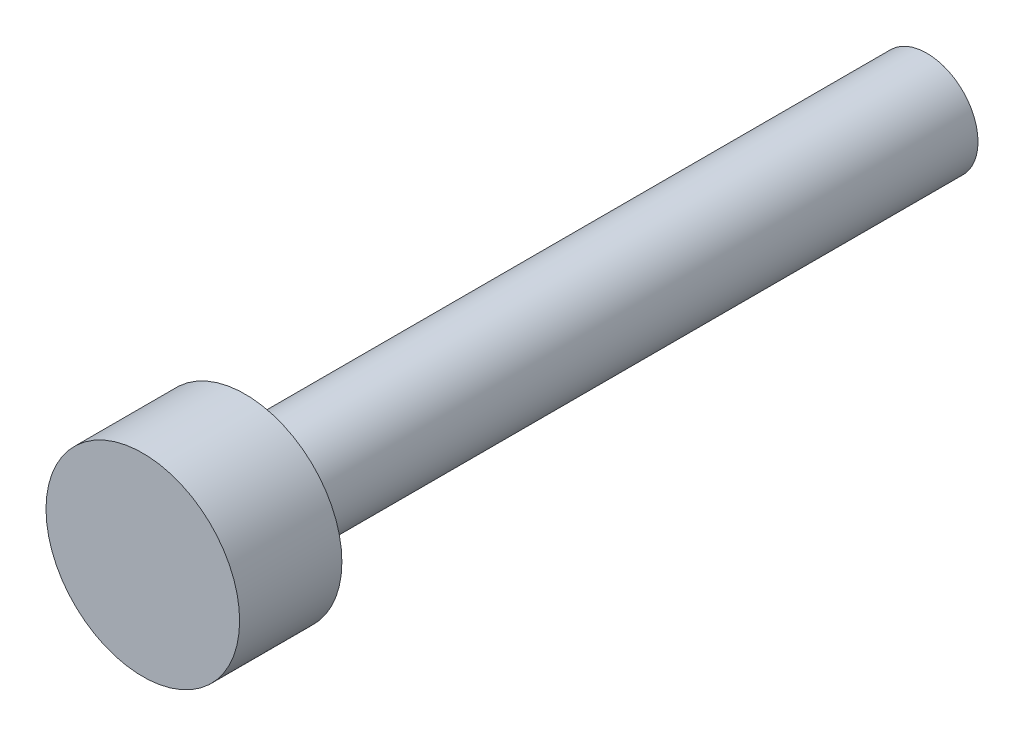
SolidWorks part; units mm, degrees
ref_plane "Front Plane" through (0, 0, 0) normal (0, 0, 1) x (1, 0, 0)
ref_plane "Top Plane" through (0, 0, 0) normal (0, 1, 0) x (1, 0, 0)
ref_plane "Right Plane" through (0, 0, 0) normal (1, 0, 0) x (0, 0, -1)
sketch "Sketch1" plane through (0, 0, 0) normal (0, 0, 1) x (1, 0, 0)
  circle A0 centre (0, 0) radius 1.5
extrude "Boss-Extrude1" add sketch "Sketch1" along normal blind 20
sketch "Sketch2" plane through (0, 0, 20) normal (0, 0, 1) x (1, 0, 0)
  circle A0 centre (0, 0) radius 2.84
extrude "Boss-Extrude2" add sketch "Sketch2" along normal blind 3
